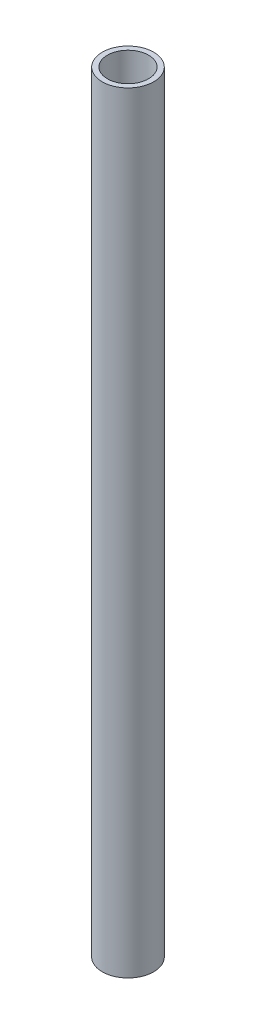
SolidWorks part; units mm, degrees
material "Thornel Mat VMA"
ref_plane "前视基准面" through (0, 0, 0) normal (0, 0, 1) x (1, 0, 0)
ref_plane "上视基准面" through (0, 0, 0) normal (0, 1, 0) x (1, 0, 0)
ref_plane "右视基准面" through (0, 0, 0) normal (1, 0, 0) x (0, 0, -1)
other "Configuration Table"
sketch "草图1" plane through (0, 0, 0) normal (0, 1, 0) x (1, 0, 0)
  circle A0 centre (0, 0) radius 5
  circle A1 centre (0, 0) radius 4
  dimension "D1" = 10
  dimension "D2" = 1
extrude "凸台-拉伸1" add sketch "草图1" along normal blind 150
